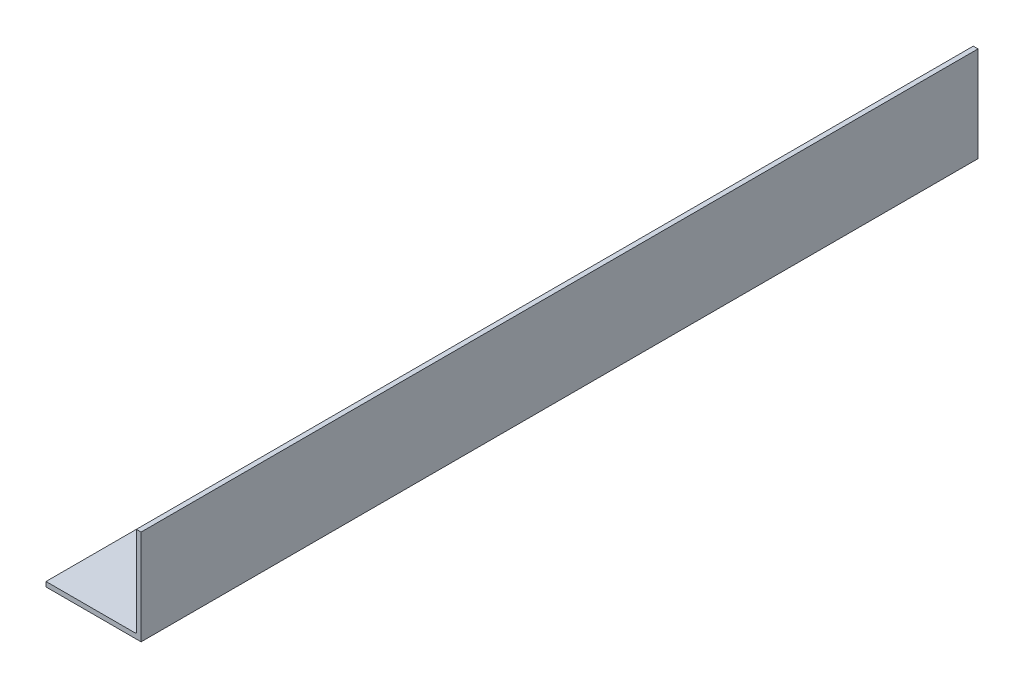
SolidWorks part; units mm, degrees
ref_plane "Front Plane" through (0, 0, 0) normal (0, 0, 1) x (1, 0, 0)
ref_plane "Top Plane" through (0, 0, 0) normal (0, 1, 0) x (1, 0, 0)
ref_plane "Right Plane" through (0, 0, 0) normal (1, 0, 0) x (0, 0, -1)
sketch "Sketch2" plane through (0, 0, 0) normal (0, 0, 1) x (1, 0, 0)
  line L0 (-15.875, 0) -> (15.875, 0)
  line L1 (15.875, 0) -> (15.875, 31.75)
  line L2 (15.875, 31.75) -> (14.2875, 31.75)
  line L3 (14.2875, 31.75) -> (14.2875, 1.9685)
  line L4 (13.9065, 1.5875) -> (-15.875, 1.5875)
  line L5 (-15.875, 0) -> (-15.875, 1.5875)
  line L6 (15.0813, 31.75) -> (15.875, 31.75) construction
  line L7 (-15.875, 0.7937) -> (-15.875, 0) construction
  arc A0 (13.9065, 1.5875) -> (14.2875, 1.9685) centre (13.9065, 1.9685) ccw
  dimension "Inner Radius" = 0.381
  dimension "Vert" = 31.75
  dimension "Horz" = 31.75
  dimension "Thickness" = 1.5875
extrude "Boss-Extrude1" add sketch "Sketch2" along normal mid plane 279.4
ref_plane "Contact Plane 1" through (0, 1.5875, 0) normal (0, 1, 0) x (1, 0, 0)
ref_plane "Contact Plane 2" through (14.2875, 0, 0) normal (-1, 0, 0) x (0, 0, 1)
